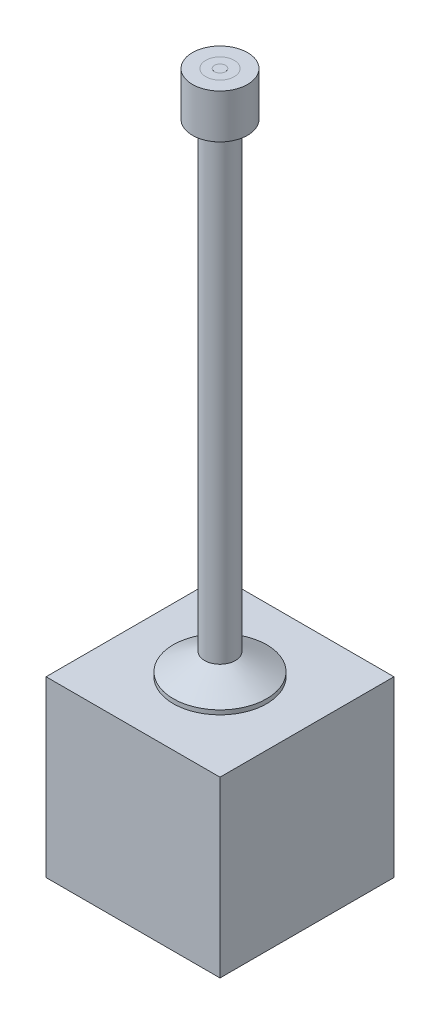
SolidWorks part; units mm, degrees
ref_plane "Alzado" through (0, 0, 0) normal (0, 0, 1) x (1, 0, 0)
ref_plane "Planta" through (0, 0, 0) normal (0, 1, 0) x (1, 0, 0)
ref_plane "Vista lateral" through (0, 0, 0) normal (1, 0, 0) x (0, 0, -1)
sketch "Croquis1" plane through (0, 0, 0) normal (0, 0, 1) x (1, 0, 0)
  line L0 (0, -22.5273) -> (0, 60.571) construction
  line L1 (5.375, 0) -> (5.375, 0.5)
  line L2 (5.375, 0.5) -> (1.78, 2.5)
  line L3 (1.78, 2.5) -> (1.78, 54.5)
  line L4 (1.78, 54.5) -> (3.1718, 55.5)
  line L5 (3.1718, 55.5) -> (3.1718, 60.571)
  line L6 (1.375, 54.9422) -> (1.375, 0)
  line L7 (1.375, 0) -> (5.375, 0)
  line L8 (0.375, 0) -> (0.375, 54.9422)
  line L9 (0.375, 54.9422) -> (0.635, 60.571)
  line L10 (0.375, 0) -> (0, 0)
  line L11 (0, 60.571) -> (0, 0)
  line L12 (0, 60.9797) -> (0, 62.2297) construction
  line L13 (3.1718, 60.571) -> (1.635, 60.571)
  line L14 (0.4604, 60.571) -> (-0.4604, 60.571) construction
  line L23 (1.375, 54.9422) -> (1.635, 60.571)
  line L26 (0.635, 60.571) -> (0.4424, 60.571)
  line L27 (0.4424, 60.571) -> (0, 60.571)
  dimension "D1" = 55
  dimension "D2" = 10.75
  dimension "D3" = 2
  dimension "D4" = 0.5
  dimension "D5" = 0.75
  dimension "D6" = 2.75
  dimension "D7" = 3.56
  dimension "D8" = 1
revolve "Revolución1" add sketch "Croquis1" angle 360 about L11
sketch "Croquis3" plane through (0, 0, 0) normal (0, 0, 1) x (1, 0, 0)
  line L0 (0, 55.5) -> (0, 0) construction
  line L1 (0.375, 54.9422) -> (0.635, 60.571)
  line L2 (0.635, 60.571) -> (-0.635, 60.571) construction
  line L3 (0.635, 60.571) -> (-0.635, 60.571) construction
  line L4 (0.635, 60.571) -> (1.635, 60.571)
  line L6 (0.635, 60.571) -> (0.4424, 60.571)
  line L7 (0.375, 0) -> (0.375, 54.9422)
  line L8 (0, 0) -> (0.375, 0)
  line L9 (0, 60.571) -> (0, 0)
  line L10 (0.375, 54.9422) -> (0.635, 60.571)
  line L12 (0.4424, 60.571) -> (0, 60.571)
  line L13 (0.375, 0) -> (0.375, 54.9422)
  line L20 (3.1718, 55.5) -> (3.1718, 60.571)
  line L21 (1.78, 54.5) -> (3.1718, 55.5)
  line L22 (1.78, 2.5) -> (1.78, 54.5)
  line L23 (5.375, 0.5) -> (1.78, 2.5)
  line L24 (5.375, 0) -> (5.375, 0.5)
  line L25 (1.375, 0) -> (5.375, 0)
  line L26 (1.375, 54.9422) -> (1.375, 0)
  line L27 (1.635, 60.571) -> (1.375, 54.9422)
  line L28 (1.635, 60.571) -> (1.375, 54.9422)
  line L29 (3.1718, 60.571) -> (1.635, 60.571)
  line L33 (0.375, 0) -> (1.375, 0)
  line L34 (1.375, 54.9422) -> (1.375, 0)
  dimension "D1" = 0
  dimension "D2" = 0
revolve "Revolución2" add sketch "Croquis3" angle 360 about L0
sketch "Croquis4" plane through (0, 0, 0) normal (0, -1, 0) x (1, 0, 0)
  line L1 (-10, -10) -> (10, -10)
  line L2 (-10, -10) -> (-10, 10)
  line L3 (-10, 10) -> (10, 10)
  line L4 (10, -10) -> (10, 10)
  line L5 (-10, -10) -> (10, 10) construction
  line L6 (-10, 10) -> (10, -10) construction
  point P0 (0, 0)
  dimension "D1" = 20
  dimension "D2" = 20
extrude "Saliente-Extruir1" add sketch "Croquis4" along normal blind 20 separate body
